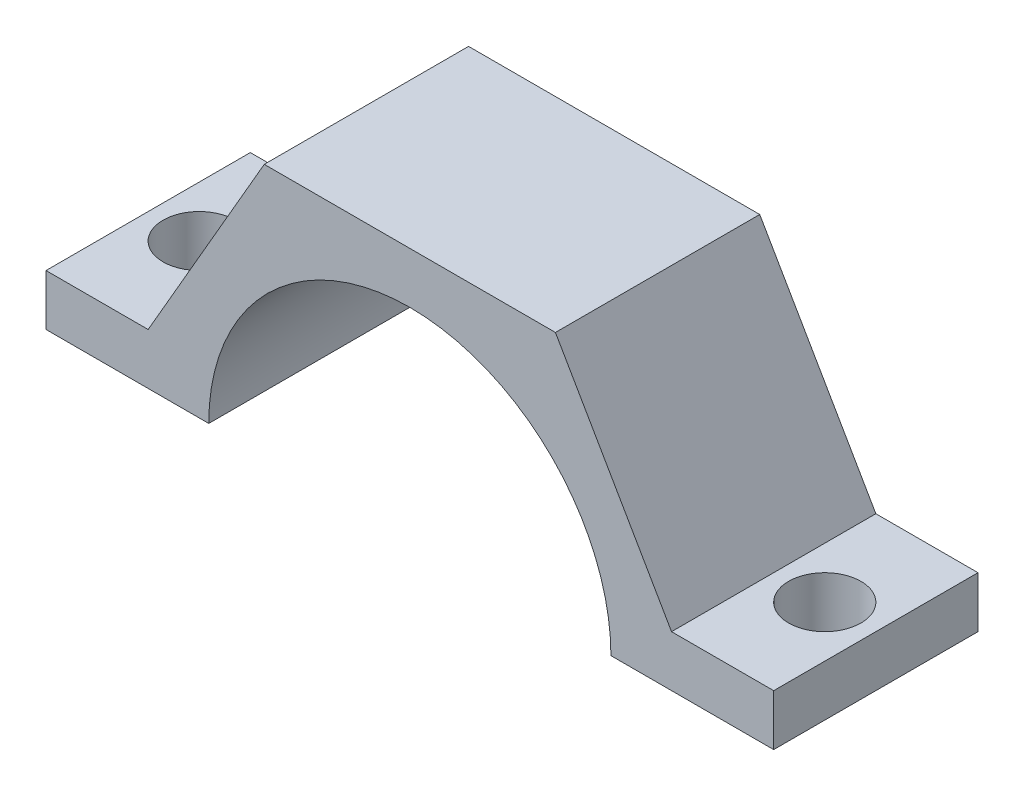
SolidWorks part; units mm, degrees
material "ABS"
ref_plane "Front Plane" through (0, 0, 0) normal (0, 0, 1) x (1, 0, 0)
ref_plane "Top Plane" through (0, 0, 0) normal (0, 1, 0) x (1, 0, 0)
ref_plane "Right Plane" through (0, 0, 0) normal (1, 0, 0) x (0, 0, -1)
sketch "Sketch2" plane through (0, 0, 0) normal (0, 0, 1) x (1, 0, 0)
  line L0 (12.5, 0) -> (22.6168, 0)
  line L1 (22.6168, 0) -> (22.6168, 3.175)
  line L2 (22.6168, 3.175) -> (16.2668, 3.175)
  line L3 (16.2668, 3.175) -> (9.05, 15.675)
  line L4 (9.05, 15.675) -> (-9.05, 15.675)
  line L5 (-9.05, 15.675) -> (-16.2668, 3.175)
  line L6 (-16.2668, 3.175) -> (-22.6168, 3.175)
  line L7 (-22.6168, 3.175) -> (-22.6168, 0)
  line L8 (-22.6168, 0) -> (-12.5, 0)
  line L9 (-16.2668, 3.175) -> (16.2668, 3.175) construction
  arc A0 (12.5, 0) -> (-12.5, 0) centre (0, 0) ccw
  circle A1 centre (0, 0) radius 15.675 construction
  arc A2 (-12.5, 0) -> (12.5, 0) centre (0, 0) ccw construction
  dimension "D1" = 25
  dimension "D3" = 3.175
  dimension "D2" = 6.35
  dimension "D4" = 3.175
  dimension "D5" = 60
extrude "Boss-Extrude1" add sketch "Sketch2" along normal blind 12.7
hole_wizard "#8 Clearance Hole1" positions "Sketch3" profile "Sketch4" hole size "#8" standard "ANSI Inch"
sketch "Sketch3" plane through (0, 3.175, 0) normal (0, 1, 0) x (1, 0, 0)
  line L0 (-19.4418, 0) -> (-19.4418, -12.7) construction
  line L1 (-16.2668, 0) -> (-22.6168, 0) construction
  line L2 (-16.2668, -12.7) -> (-22.6168, -12.7) construction
  line L4 (19.4418, 0) -> (19.4418, -12.7) construction
  line L5 (22.6168, 0) -> (16.2668, 0) construction
  line L6 (22.6168, -12.7) -> (16.2668, -12.7) construction
  point P16 (-19.4418, -6.35)
  point P18 (19.4418, -6.35)
sketch "Sketch4" plane through (19.4418, 3.175, 6.35) normal (1, 0, 0) x (0, 0, 1)
  line L0 (0, 0) -> (0, 62.8187)
  line L1 (0, 62.8187) -> (2.2479, 61.468)
  line L2 (2.2479, 61.468) -> (2.2479, 0)
  line L5 (2.2479, 0) -> (0, 0)
  line L10 (0, 62.8187) -> (-2.2479, 61.468) construction
  line L11 (0, -6.35) -> (0, 107.95) construction
  dimension "Hole Dia." = 4.4958
  dimension "Hole Depth" = 61.468
  dimension "Drill Angle" = 118
